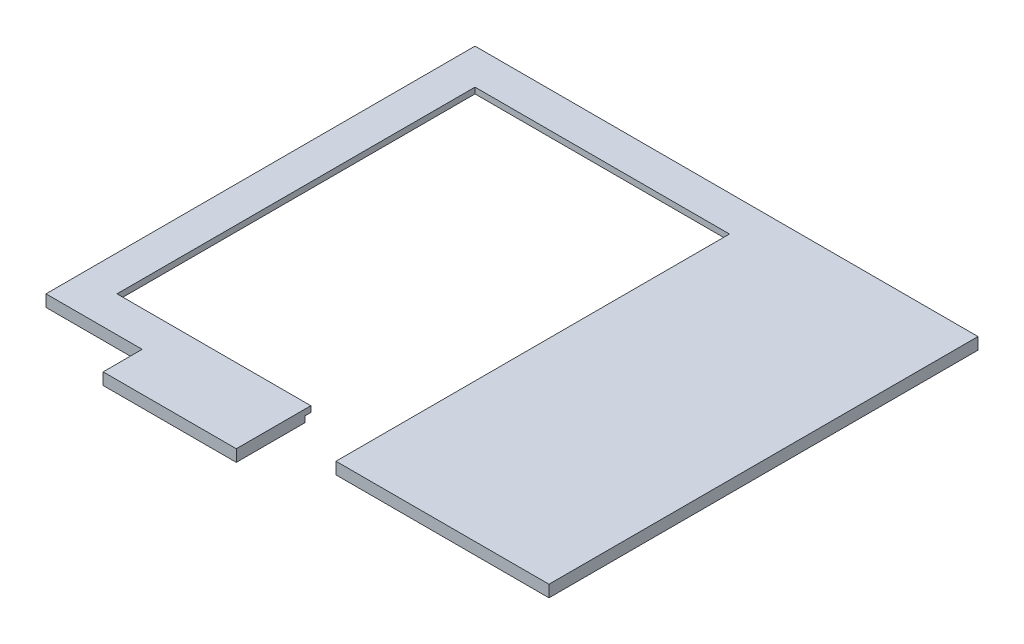
SolidWorks part; units mm, degrees
ref_plane "Front Plane" through (0, 0, 0) normal (0, 0, 1) x (1, 0, 0)
ref_plane "Top Plane" through (0, 0, 0) normal (0, 1, 0) x (1, 0, 0)
ref_plane "Right Plane" through (0, 0, 0) normal (1, 0, 0) x (0, 0, -1)
sketch "Sketch1" plane through (0, 55.3432, 0) normal (0, 1, 0) x (1, 0, 0)
  line L8 (-104.6818, -229.0452) -> (-59.6818, -229.0452)
  line L9 (-59.6818, -229.0452) -> (-59.6818, -215.8616)
  line L10 (-59.6818, -215.8616) -> (32.8182, -215.8616)
  line L11 (32.8182, -215.8616) -> (32.8182, -70.8616)
  line L12 (32.8182, -70.8616) -> (-137.1818, -70.8616)
  line L13 (-137.1818, -70.8616) -> (-137.1818, -215.8616)
  line L14 (-137.1818, -215.8616) -> (-104.6818, -215.8616)
  line L15 (-104.6818, -215.8616) -> (-104.6818, -229.0452)
  line L16 (-104.6818, -229.0452) -> (-59.6818, -229.0452)
  line L17 (-59.6818, -229.0452) -> (-59.6818, -215.8616)
  line L18 (-59.6818, -215.8616) -> (32.8182, -215.8616)
  line L19 (32.8182, -215.8616) -> (32.8182, -70.8616)
  line L20 (32.8182, -70.8616) -> (-137.1818, -70.8616)
  line L21 (-137.1818, -70.8616) -> (-137.1818, -215.8616)
  line L22 (-137.1818, -215.8616) -> (-104.6818, -215.8616)
  line L23 (-104.6818, -215.8616) -> (-104.6818, -229.0452)
  line M9 (-104.6818, -229.0452) -> (-59.6818, -229.0452)
  line M10 (-59.6818, -229.0452) -> (-59.6818, -215.8616)
  line M11 (-59.6818, -215.8616) -> (32.8182, -215.8616)
  line M12 (32.8182, -215.8616) -> (32.8182, -70.8616)
  line M13 (32.8182, -70.8616) -> (-137.1818, -70.8616)
  line M14 (-137.1818, -70.8616) -> (-137.1818, -215.8616)
  line M15 (-137.1818, -215.8616) -> (-104.6818, -215.8616)
  line M16 (-104.6818, -215.8616) -> (-104.6818, -229.0452)
  line M17 (-37.1818, -80.8616) -> (-37.1818, -205.8616)
  line M18 (-37.1818, -205.8616) -> (-127.1818, -205.8616)
  line M19 (-127.1818, -205.8616) -> (-127.1818, -80.8616)
  line M20 (-127.1818, -80.8616) -> (-37.1818, -80.8616)
  dimension "D1" = 0
extrude "Boss-Extrude1" add sketch "Sketch1" along normal blind 4 contours M16 M9 M10 M11 M12 M13 M14 M15 M20 M17 M18 M19
sketch "Sketch2" plane through (0, 59.3432, 0) normal (0, 1, 0) x (1, 0, 0)
  line L0 (-127.1818, -80.8616) -> (-37.1818, -80.8616) construction
  line L1 (-127.1818, -205.8616) -> (-127.1818, -80.8616) construction
  line L2 (-37.1818, -205.8616) -> (-127.1818, -205.8616) construction
  line L3 (-37.1818, -80.8616) -> (-37.1818, -205.8616) construction
  line L4 (-127.1818, -80.8616) -> (-37.1818, -80.8616)
  line L5 (-127.1818, -205.8616) -> (-127.1818, -80.8616)
  line L6 (-37.1818, -205.8616) -> (-127.1818, -205.8616)
  line L7 (-37.1818, -80.8616) -> (-37.1818, -205.8616)
  line L8 (-125.1818, -203.8616) -> (-125.1818, -82.8616)
  line L9 (-125.1818, -82.8616) -> (-39.1818, -82.8616)
  line L10 (-39.1818, -82.8616) -> (-39.1818, -203.8616)
  line L11 (-39.1818, -203.8616) -> (-125.1818, -203.8616)
  dimension "D1" = 2
extrude "Boss-Extrude2" add sketch "Sketch2" against normal up to surface (2 mm away)
sketch "Sketch3" plane through (0, 59.3432, 0) normal (0, 1, 0) x (1, 0, 0)
  line L0 (-59.6818, -234.0452) -> (-59.6818, -150.3652) construction
  line L1 (-59.6818, -203.8616) -> (-39.1818, -203.8616)
  line L2 (-59.6818, -203.8616) -> (-59.6818, -215.8616)
  line L3 (-59.6818, -215.8616) -> (-39.1818, -215.8616)
  line L4 (-39.1818, -203.8616) -> (-39.1818, -215.8616)
  line L5 (-125.1818, -203.8616) -> (-39.1818, -203.8616) construction
  line L6 (-59.6818, -215.8616) -> (32.8182, -215.8616) construction
  line L7 (-39.1818, -203.8616) -> (-39.1818, -82.8616) construction
extrude "Cut-Extrude1" cut sketch "Sketch3" against normal blind 10 contours L2 L1 L4 L3
